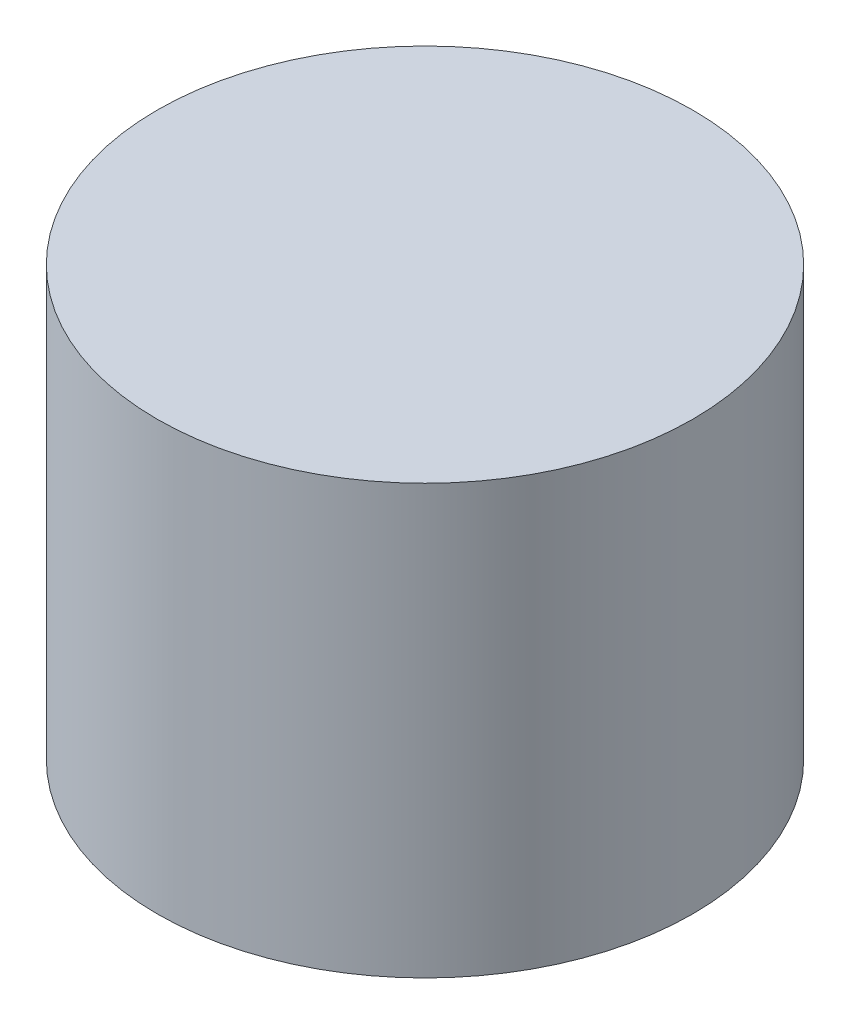
SolidWorks part; units mm, degrees
ref_plane "Спереди" through (0, 0, 0) normal (0, 0, 1) x (1, 0, 0)
ref_plane "Сверху" through (0, 0, 0) normal (0, 1, 0) x (1, 0, 0)
ref_plane "Справа" through (0, 0, 0) normal (1, 0, 0) x (0, 0, -1)
other "Configuration Table"
sketch "Sketch1" plane through (0, 0, 0) normal (0, 1, 0) x (1, 0, 0)
  circle A0 centre (0, 0) radius 12.5
  dimension "D1" = 25
extrude "Boss-Extrude1" add sketch "Sketch1" along normal blind 20
